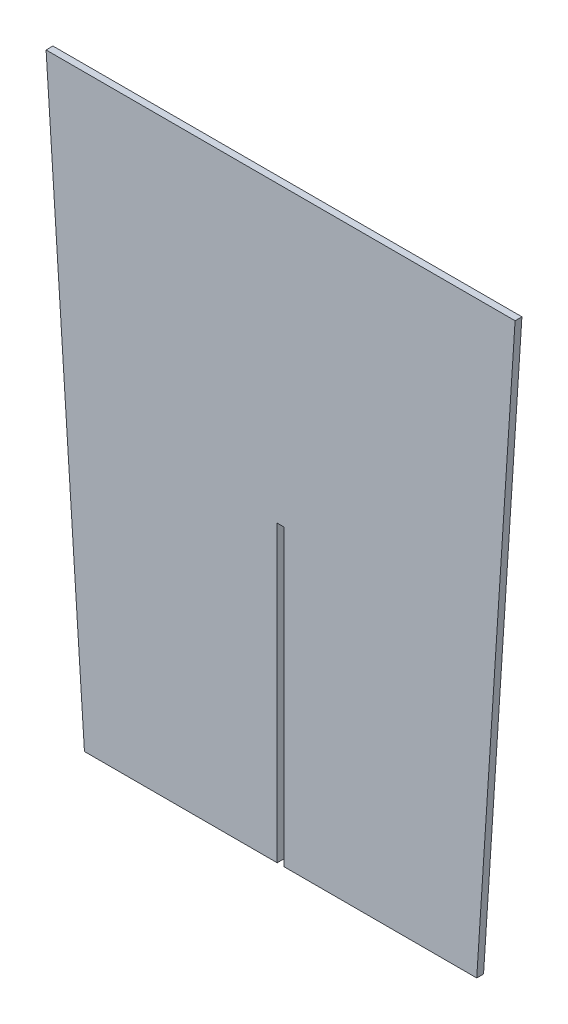
SolidWorks part; units mm, degrees
ref_plane "Front Plane" through (0, 0, 0) normal (0, 0, 1) x (1, 0, 0)
ref_plane "Top Plane" through (0, 0, 0) normal (0, 1, 0) x (1, 0, 0)
ref_plane "Right Plane" through (0, 0, 0) normal (1, 0, 0) x (0, 0, -1)
sketch "Sketch4" plane through (0, 0, 0) normal (0, 0, 1) x (1, 0, 0)
  line L0 (0, 0) -> (230, 0)
  line L1 (115, 0) -> (115, 345)
  line L2 (252.5, 345) -> (-22.5, 345)
  line L3 (-22.5, 345) -> (0, 0)
  line L4 (115, 345) -> (115, -53.3069) construction
  line L5 (252.5, 345) -> (230, 0)
  line L6 (115, 172.5) -> (117, 172.5)
  line L7 (117, 172.5) -> (117, 0)
  line L8 (117, 0) -> (113, 0)
  line L9 (113, 0) -> (113, 172.5)
  line L10 (113, 172.5) -> (115, 172.5)
  dimension "D1" = 115
  dimension "D2" = 345
  dimension "D3" = 137.5
  dimension "D4" = 2
  dimension "D5" = 2
extrude "Boss-Extrude1" add sketch "Sketch4" along normal blind 4 contours L5 L2 L1 L0 | L2 L3 L0 L1
